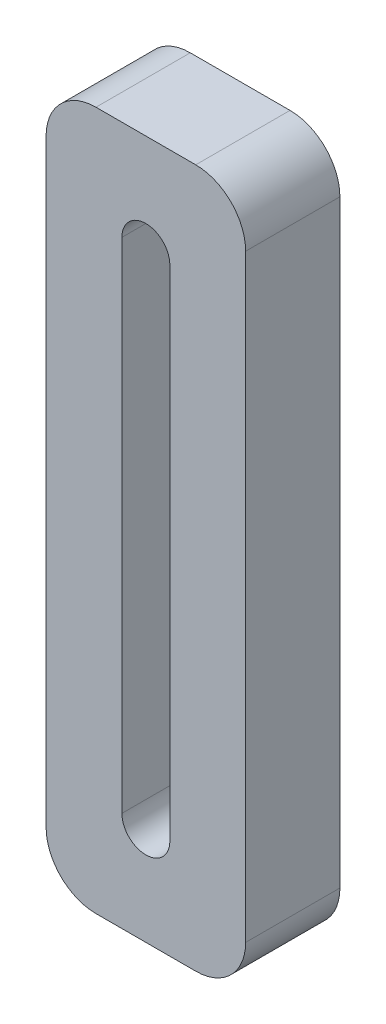
SolidWorks part; units mm, degrees
ref_plane "Front Plane" through (0, 0, 0) normal (0, 0, 1) x (1, 0, 0)
ref_plane "Top Plane" through (0, 0, 0) normal (0, 1, 0) x (1, 0, 0)
ref_plane "Right Plane" through (0, 0, 0) normal (1, 0, 0) x (0, 0, -1)
sketch "Sketch1" plane through (0, 0, 0) normal (0, 0, 1) x (1, 0, 0)
  line L0 (0, 15.875) -> (0, -15.875) construction
  line L1 (-6.35, -22.225) -> (6.35, -22.225)
  line L2 (-6.35, -22.225) -> (-6.35, 22.225)
  line L3 (-6.35, 22.225) -> (6.35, 22.225)
  line L4 (6.35, -22.225) -> (6.35, 22.225)
  line L5 (-6.35, -22.225) -> (6.35, 22.225) construction
  line L6 (-6.35, 22.225) -> (6.35, -22.225) construction
  line L7 (1.5269, 15.875) -> (1.5269, -15.875)
  line L8 (-1.5269, 15.875) -> (-1.5269, -15.875)
  arc A0 (1.5269, 15.875) -> (-1.5269, 15.875) centre (0, 15.875) ccw
  arc A1 (-1.5269, -15.875) -> (1.5269, -15.875) centre (0, -15.875) ccw
  point P0 (0, 0)
  point P8 (0, 0)
  dimension "D3" = 3.0538
  dimension "D1" = 44.45
  dimension "D2" = 12.7
  dimension "D4" = 6.35
  dimension "D5" = 6.35
extrude "Boss-Extrude1" add sketch "Sketch1" along normal mid plane 6
fillet "Fillet1" radius 3.175 4 edges at (6.35, -22.225, 0) (-6.35, -22.225, 0) (6.35, 22.225, 0) (-6.35, 22.225, 0)
